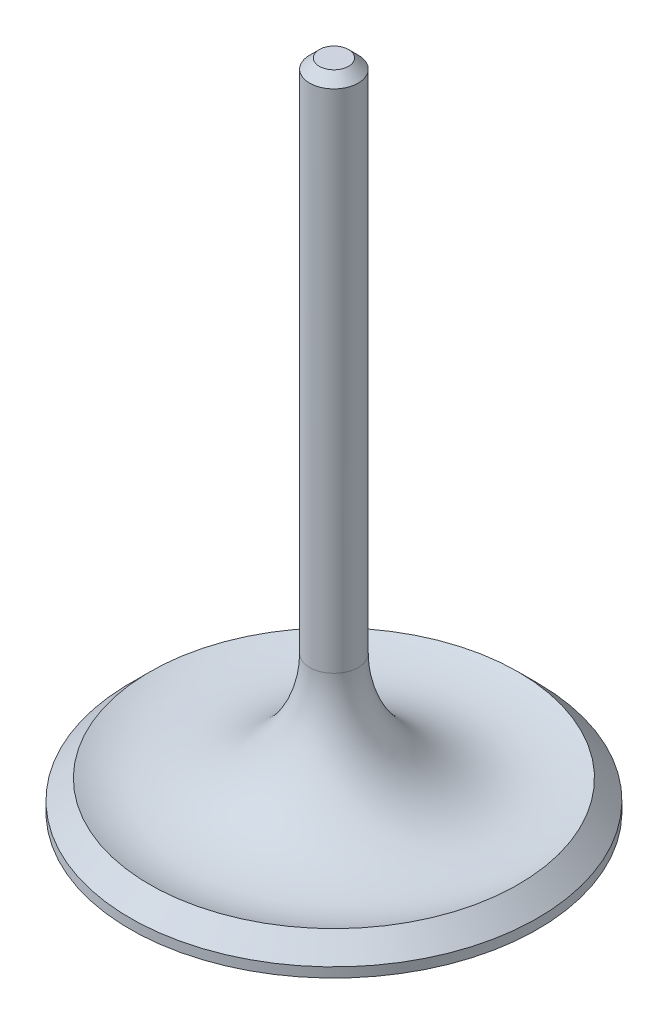
SolidWorks part; units mm, degrees
ref_plane "Front Plane" through (0, 0, 0) normal (0, 0, 1) x (1, 0, 0)
ref_plane "Top Plane" through (0, 0, 0) normal (0, 1, 0) x (1, 0, 0)
ref_plane "Right Plane" through (0, 0, 0) normal (1, 0, 0) x (0, 0, -1)
sketch "Sketch1" plane through (0, 0, 0) normal (0, 0, 1) x (1, 0, 0)
  line L0 (0, 0) -> (0, 85.5)
  line L1 (0, 85.5) -> (3.18, 85.5)
  line L2 (3.18, 85.5) -> (3.18, 17.9547)
  line L3 (24.13, 3.81) -> (26.67, 1.27)
  line L4 (26.67, 1.27) -> (26.67, 0)
  line L5 (26.67, 0) -> (0, 0)
  arc A0 (3.18, 17.9547) -> (24.13, 3.81) centre (18.43, 17.9547) ccw
  dimension "D3" = 15.25
  dimension "D1" = 85.5
  dimension "D2" = 3.18
  dimension "D4" = 1.27
  dimension "D5" = 3.81
  dimension "D6" = 45
  dimension "D7" = 26.67
revolve "Revolve2" add sketch "Sketch1" angle 360 about L0
chamfer "Chamfer1" distance 1.27 angle 45 1 edges at (0, 85.5, -3.18)
